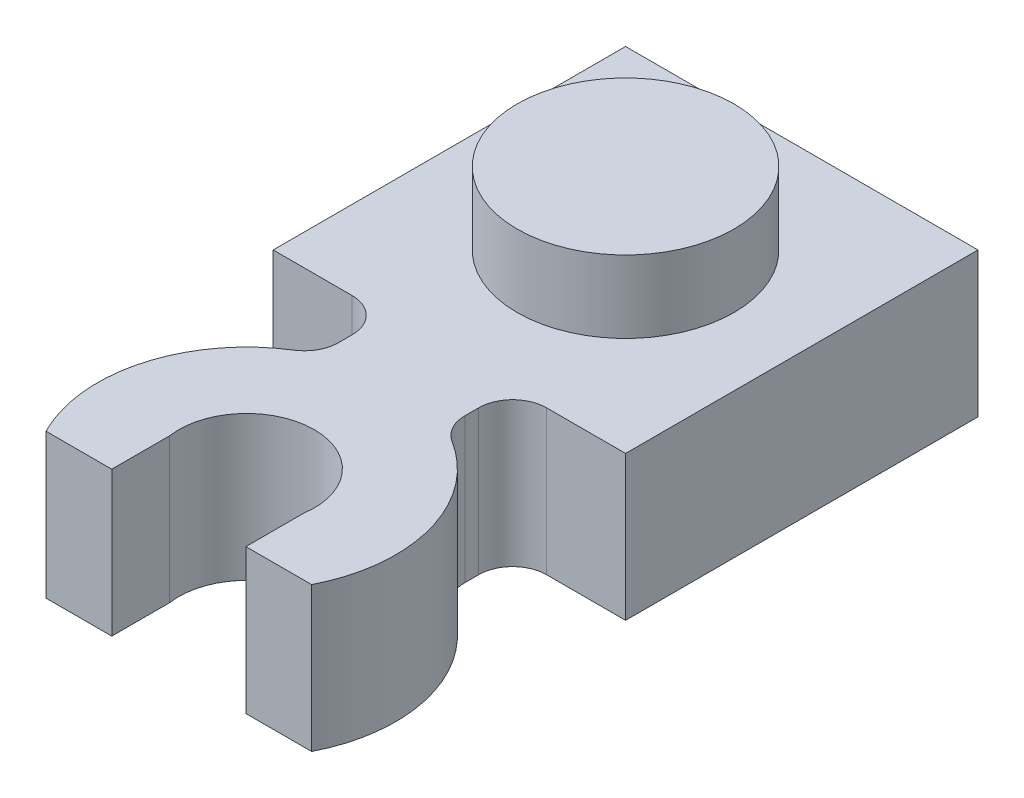
SolidWorks part; units mm, degrees
material "ABS"
ref_plane "Front Plane" through (0, 0, 0) normal (0, 0, 1) x (1, 0, 0)
ref_plane "Top Plane" through (0, 0, 0) normal (0, 1, 0) x (1, 0, 0)
ref_plane "Right Plane" through (0, 0, 0) normal (1, 0, 0) x (0, 0, -1)
sketch "Sketch1" plane through (0, 0, 0) normal (0, 0, 1) x (1, 0, 0)
  line L1 (0, 0) -> (7.8, 0)
  line L2 (0, 0) -> (0, 3.2)
  line L3 (0, 3.2) -> (7.8, 3.2)
  line L4 (7.8, 0) -> (7.8, 3.2)
  line L5 (0, 0) -> (7.8, 3.2) construction
  line L6 (0, 3.2) -> (7.8, 0) construction
  point P4 (3.9, 1.6)
  dimension "D1" = 7.8
  dimension "D2" = 3.2
extrude "Boss-Extrude1" add sketch "Sketch1" against normal blind 7.8
sketch "Sketch2" plane through (0, 3.2, 0) normal (0, 1, 0) x (1, 0, 0)
  line L0 (7.8, 0) -> (0, 0) construction
  circle A0 centre (3.9, 3.9) radius 2.4
  dimension "D1" = 4.8
  dimension "D2" = 3.9
  dimension "D3" = 3.9
extrude "Boss-Extrude2" add sketch "Sketch2" along normal blind 1.6
shell "Shell1" thickness 0.7
sketch "Sketch3" plane through (0, 0, 0) normal (0, 0, 1) x (1, 0, 0)
  line L0 (2.5, 3.2) -> (5.3, 3.2)
  line L1 (7.8, 3.2) -> (0, 3.2) construction
  line L2 (5.3, 3.2) -> (5.3, 0)
  line L3 (0, 0) -> (7.8, 0) construction
  line L4 (5.3, 0) -> (2.5, 0)
  line L5 (2.5, 0) -> (2.5, 3.2)
  line L6 (7.8, 0) -> (7.8, 3.2) construction
  line L7 (0, 3.2) -> (0, 0) construction
  dimension "D1" = 2.5
  dimension "D2" = 2.5
extrude "Boss-Extrude3" add sketch "Sketch3" along normal blind 1.5
ref_plane "Plane1" through (0, 3.2, 0) normal (0, 1, 0) x (1, 0, 0)
sketch "Sketch5" plane through (0, 3.2, 0) normal (0, 1, 0) x (1, 0, 0)
  line L0 (0.9606, -5.9883) -> (2.4161, -5.9883)
  line L1 (2.4161, -5.9883) -> (2.4161, -4.7073)
  line L2 (6.8394, -5.9883) -> (5.3839, -5.9883)
  line L3 (5.3839, -5.9883) -> (5.3839, -4.7073)
  arc A0 (6.8394, -5.9883) -> (0.9606, -5.9883) centre (3.9, -4.4883) ccw
  arc A1 (5.3839, -4.7073) -> (2.4161, -4.7073) centre (3.9, -4.4883) ccw
  dimension "D1" = 1.8
  dimension "D2" = 1.5
  dimension "D3" = 1.4555
extrude "Boss-Extrude4" add sketch "Sketch5" against normal up to surface (3.2 mm away) up to face at (3.9, 0, -1.575)
fillet "Fillet1" radius 0.75 2 edges at (2.5, 1.6, 0) (2.5, 1.6, 1.5)
fillet "Fillet2" radius 0.75 2 edges at (5.3, 1.6, 1.5) (5.3, 1.6, 0)
sketch "Sketch6" plane through (0, 0, 0) normal (0, -1, 0) x (1, 0, 0)
  circle A0 centre (3.7901, 0.3427) radius 0.4249
  arc A1 (2.4161, 4.7073) -> (5.3839, 4.7073) centre (3.9, 4.4883) ccw construction
  dimension "D1" = 0.8499
  dimension "D2" = 1.3528
  dimension "D3" = 4.1471
extrude "Cut-Extrude1" cut sketch "Sketch6" against normal blind 1.6
